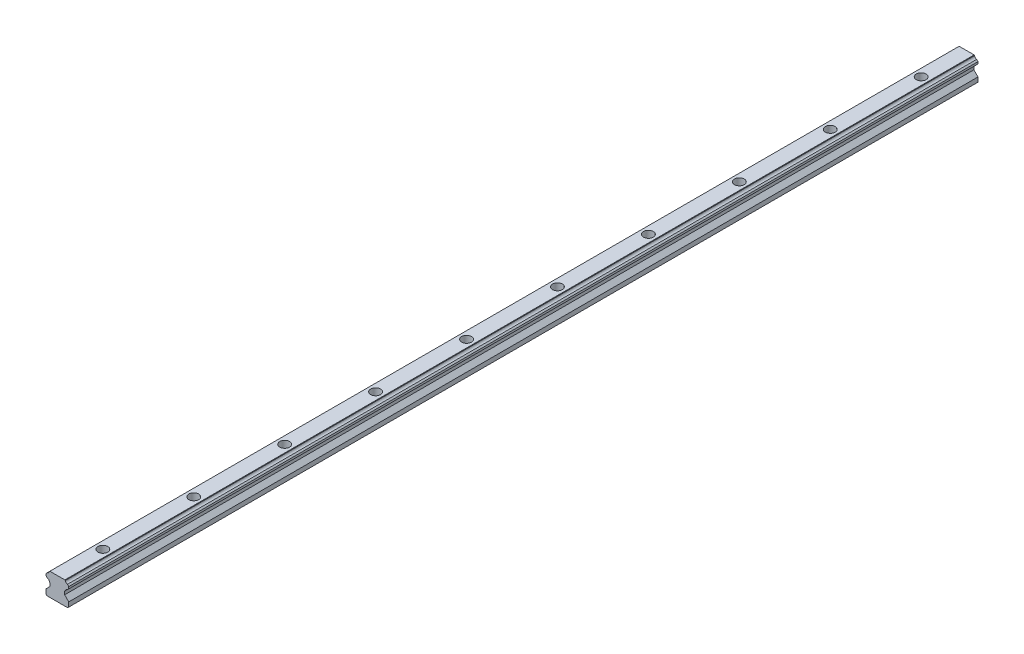
SolidWorks part; units mm, degrees
ref_plane "Спереди" through (0, 0, 0) normal (0, 0, 1) x (1, 0, 0)
ref_plane "Сверху" through (0, 0, 0) normal (0, 1, 0) x (1, 0, 0)
ref_plane "Справа" through (0, 0, 0) normal (1, 0, 0) x (0, 0, -1)
sketch "Model" plane through (0, 0, 0) normal (0, 0, 1) x (1, 0, 0)
  line L7 (6.8, 0) -> (7.5, 0.7)
  line L8 (7.5, 0.7) -> (7.5, 3.6994)
  line L9 (7.5, 3.6994) -> (4.7998, 6.3996)
  line L10 (4.7998, 6.3996) -> (4.7998, 8.4091)
  line L11 (4.7998, 8.4091) -> (5.2008, 8.8101)
  line L12 (6.6481, 10.2574) -> (7.5, 11.1093)
  line L13 (7.5, 11.1093) -> (7.5, 12.4495)
  line L14 (7.5, 12.4495) -> (6.6345, 13.315)
  line L15 (5.2023, 14.7472) -> (4.9495, 15)
  line L16 (4.9495, 15) -> (-4.9495, 15)
  line L17 (-4.9495, 15) -> (-5.2023, 14.7472)
  line L18 (-6.6345, 13.315) -> (-7.5, 12.4495)
  line L19 (-7.5, 12.4495) -> (-7.5, 11.1093)
  line L20 (-7.5, 11.1093) -> (-6.6481, 10.2574)
  line L21 (-5.2008, 8.8101) -> (-4.7998, 8.4091)
  line L22 (-4.7998, 8.4091) -> (-4.7998, 6.3996)
  line L23 (-4.7998, 6.3996) -> (-7.5, 3.6994)
  line L24 (-7.5, 3.6994) -> (-7.5, 0.7)
  line L25 (-7.5, 0.7) -> (-6.8, 0)
  line L26 (-6.8, 0) -> (6.8, 0)
  arc A0 (6.6481, 10.2574) -> (5.2008, 8.8101) centre (6.8215, 8.6367) ccw
  arc A1 (5.2023, 14.7472) -> (6.6345, 13.315) centre (6.8215, 14.9342) ccw
  arc A2 (-6.6345, 13.315) -> (-5.2023, 14.7472) centre (-6.8215, 14.9342) ccw
  arc A3 (-5.2008, 8.8101) -> (-6.6481, 10.2574) centre (-6.8215, 8.6367) ccw
extrude "Бобышка-Вытянуть1" add sketch "Model" along normal blind 600
sketch "Эскиз2" plane through (0, 15, 0) normal (0, 1, 0) x (1, 0, 0)
  line L0 (0, 43.9966) -> (0, -648.9514) construction
  line L1 (4.9495, 0) -> (-4.9495, 0) construction
  circle A0 centre (0, -30) radius 3.25
  circle A1 centre (0, -90) radius 3.25
  circle A2 centre (0, -150) radius 3.25
  circle A3 centre (0, -210) radius 3.25
  circle A4 centre (0, -270) radius 3.25
  circle A5 centre (0, -330) radius 3.25
  circle A6 centre (0, -390) radius 3.25
  circle A7 centre (0, -450) radius 3.25
  circle A8 centre (0, -510) radius 3.25
  circle A9 centre (0, -570) radius 3.25
  dimension "D1" = 10
  dimension "D2" = 30
extrude "Вырез-Вытянуть1" cut sketch "Эскиз2" against normal blind 5.3
sketch "Эскиз3" plane through (0, 9.7, 0) normal (0, 1, 0) x (1, 0, 0)
  circle A0 centre (0, -30) radius 2.25
  circle A1 centre (0, -90) radius 2.25
  circle A2 centre (0, -150) radius 2.25
  circle A3 centre (0, -210) radius 2.25
  circle A4 centre (0, -270) radius 2.25
  circle A5 centre (0, -330) radius 2.25
  circle A6 centre (0, -390) radius 2.25
  circle A7 centre (0, -450) radius 2.25
  circle A8 centre (0, -510) radius 2.25
  circle A9 centre (0, -570) radius 2.25
  dimension "D1" = 10
extrude "Вырез-Вытянуть2" cut sketch "Эскиз3" against normal through all
